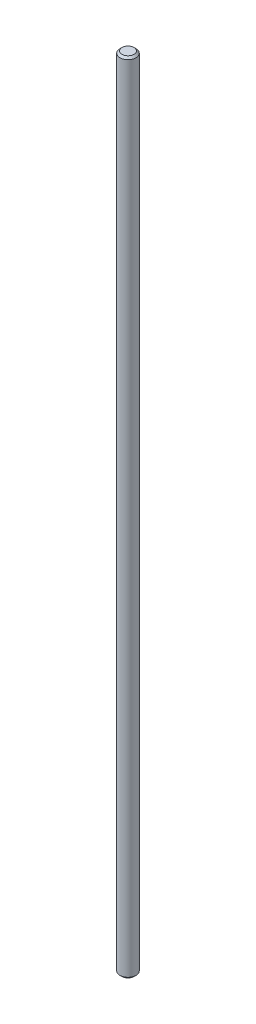
SolidWorks part; units mm, degrees
material "Chrome Stainless Steel"
ref_plane "Front Plane" through (0, 0, 0) normal (0, 0, 1) x (1, 0, 0)
ref_plane "Top Plane" through (0, 0, 0) normal (0, 1, 0) x (1, 0, 0)
ref_plane "Right Plane" through (0, 0, 0) normal (1, 0, 0) x (0, 0, -1)
sketch "Sketch2" plane through (0, 0, 0) normal (0, 1, 0) x (1, 0, 0)
  circle A0 centre (0, 0) radius 4
  dimension "D1" = 8
extrude "Boss-Extrude1" add sketch "Sketch2" along normal mid plane 400
chamfer "Chamfer1" distance 1 angle 45 2 edges at (0, -200, 4) (0, 200, 4)
